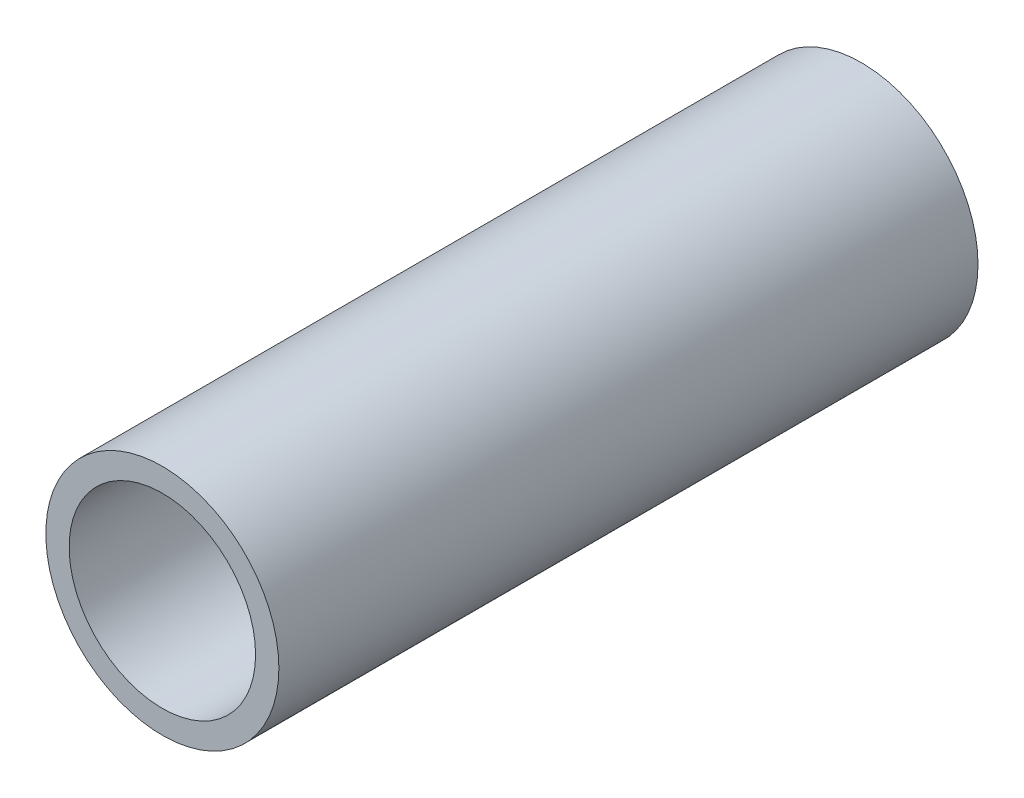
SolidWorks part; units mm, degrees
ref_plane "Front Plane" through (0, 0, 0) normal (0, 0, 1) x (1, 0, 0)
ref_plane "Top Plane" through (0, 0, 0) normal (0, 1, 0) x (1, 0, 0)
ref_plane "Right Plane" through (0, 0, 0) normal (1, 0, 0) x (0, 0, -1)
sketch "Sketch1" plane through (0, 0, 0) normal (0, 0, 1) x (1, 0, 0)
  circle A0 centre (0, 0) radius 12.5
  circle A1 centre (0, 0) radius 10
  dimension "D1" = 25
  dimension "D2" = 2.5
extrude "Boss-Extrude1" add sketch "Sketch1" along normal mid plane 75
